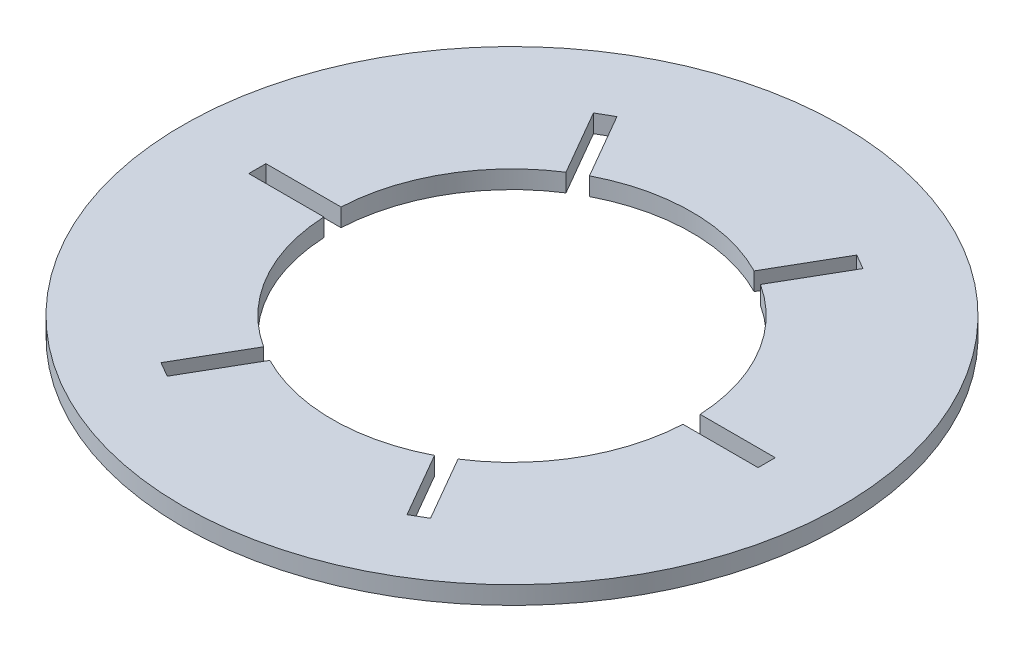
SolidWorks part; units mm, degrees
ref_plane "Front Plane" through (0, 0, 0) normal (0, 0, 1) x (1, 0, 0)
ref_plane "Top Plane" through (0, 0, 0) normal (0, 1, 0) x (1, 0, 0)
ref_plane "Right Plane" through (0, 0, 0) normal (1, 0, 0) x (0, 0, -1)
sketch "Sketch1" plane through (0, 0, 0) normal (0, 1, 0) x (1, 0, 0)
  circle A0 centre (0, 0) radius 55
  dimension "D1" = 110
extrude "Boss-Extrude1" add sketch "Sketch1" along normal blind 3
sketch "Sketch2" plane through (0, 3, 0) normal (0, 1, 0) x (1, 0, 0)
  circle A0 centre (0, 0) radius 30
  dimension "D1" = 60
extrude "Cut-Extrude1" cut sketch "Sketch2" against normal blind 3
sketch "Sketch3" plane through (0, 3, 0) normal (0, 1, 0) x (1, 0, 0)
  line L0 (73.8169, 0) -> (-73.8169, 0) construction
  line L1 (0, -87.0918) -> (0, 87.0918) construction
  line L3 (-42.5, 1.435) -> (-17.5, 1.435)
  line L4 (-42.5, 1.435) -> (-42.5, -1.435)
  line L5 (-42.5, -1.435) -> (-17.5, -1.435)
  line L6 (-17.5, 1.435) -> (-17.5, -1.435)
  line L7 (-42.5, 1.435) -> (-17.5, -1.435) construction
  line L8 (-42.5, -1.435) -> (-17.5, 1.435) construction
  circle A0 centre (0, 0) radius 30 construction
  point P0 (-30, 0)
  point P6 (0, 0)
  point P10 (0, 0)
  dimension "D1" = 2.87
  dimension "D2" = 25
extrude "Cut-Extrude2" cut sketch "Sketch3" against normal blind 3
pattern_circular "CirPattern1" count 6 over 360 about axis through (0, 0, 0) along (0, 1, 0) of "Cut-Extrude2"
